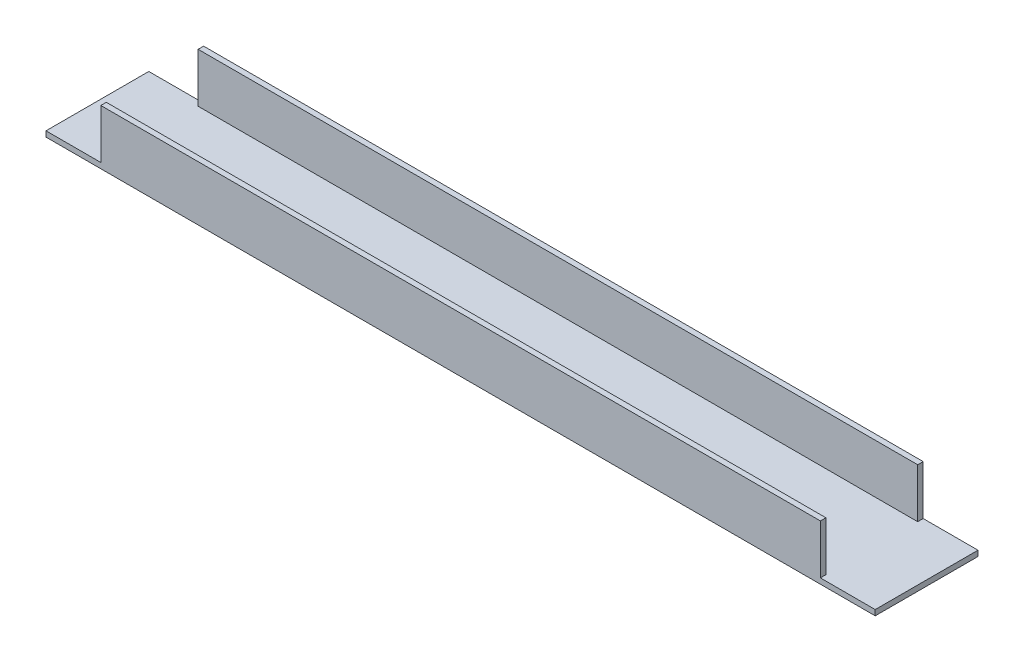
SolidWorks part; units mm, degrees
ref_plane "정면" through (0, 0, 0) normal (0, 0, 1) x (1, 0, 0)
ref_plane "윗면" through (0, 0, 0) normal (0, 1, 0) x (1, 0, 0)
ref_plane "우측면" through (0, 0, 0) normal (1, 0, 0) x (0, 0, -1)
sketch "스케치2" plane through (0, 0, 0) normal (0, 1, 0) x (1, 0, 0)
  line L1 (0, 0) -> (605, 0)
  line L2 (0, 0) -> (0, 75)
  line L3 (0, 75) -> (605, 75)
  line L4 (605, 0) -> (605, 75)
  dimension "D1" = 605
  dimension "D2" = 75
extrude "보스-돌출1" add sketch "스케치2" along normal blind 4
sketch "스케치3" plane through (0, 4, 0) normal (0, 1, 0) x (1, 0, 0)
  line L0 (0, 0) -> (605, 0) construction
  line L1 (40, 0) -> (565, 0)
  line L2 (40, 0) -> (40, 4)
  line L3 (40, 4) -> (565, 4)
  line L4 (565, 0) -> (565, 4)
  line L5 (605, 75) -> (0, 75) construction
  line L6 (565, 75) -> (40, 75)
  line L7 (565, 75) -> (565, 71)
  line L8 (565, 71) -> (40, 71)
  line L9 (40, 75) -> (40, 71)
  line L10 (0, 75) -> (0, 0) construction
  line L11 (605, 0) -> (605, 75) construction
  dimension "D1" = 40
  dimension "D2" = 40
  dimension "D3" = 4
  dimension "D4" = 4
extrude "보스-돌출2" add sketch "스케치3" along normal blind 40 from surface at -4 starting at face at (302.5, 0, -37.5)
